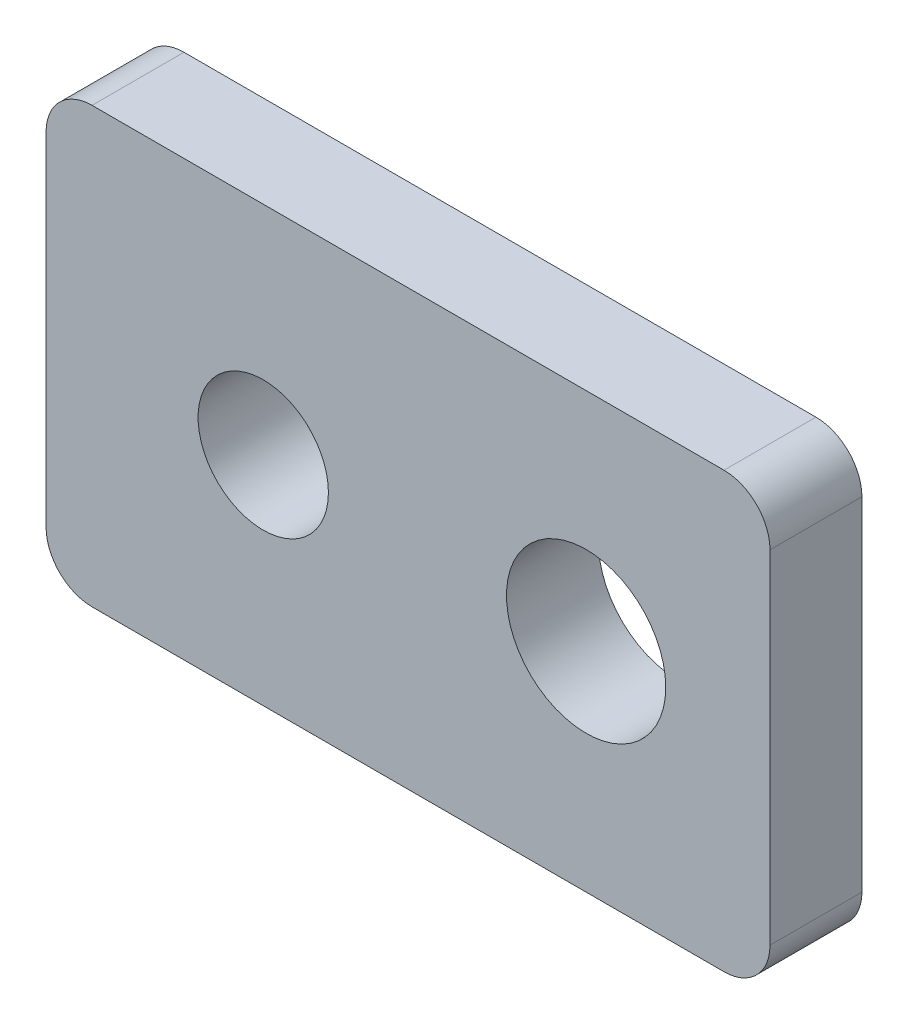
SolidWorks part; units mm, degrees
material "3003-H14"
ref_plane "X-Y Datum" through (0, 0, 0) normal (0, 0, 1) x (1, 0, 0)
ref_plane "X-Z Datum" through (0, 0, 0) normal (0, 1, 0) x (1, 0, 0)
ref_plane "Y-Z Datum" through (0, 0, 0) normal (1, 0, 0) x (0, 0, -1)
sketch "Sketch1" plane through (0, 0, 0) normal (0, 0, 1) x (1, 0, 0)
  line L0 (6.15, 7.5) -> (6.15, -7.5) construction
  line L1 (-12.5, 7.5) -> (12.5, 7.5)
  line L2 (-12.5, 7.5) -> (-12.5, -7.5)
  line L3 (-12.5, -7.5) -> (12.5, -7.5)
  line L4 (12.5, 7.5) -> (12.5, -7.5)
  line L5 (-12.5, 7.5) -> (12.5, -7.5) construction
  line L6 (-12.5, -7.5) -> (12.5, 7.5) construction
  line L7 (-12.5, 0) -> (12.5, 0) construction
  circle A0 centre (6.15, 0) radius 2.5
  point P0 (0, 0)
  dimension "D3" = 5
  dimension "D4" = 6.35
  dimension "D1" = 15
  dimension "D2" = 25
extrude "Boss-Extrude1" add sketch "Sketch1" along normal blind 3.175 contours A0 | L4 L1 L2 L3 A0
hole_wizard "M5 Clearance Hole1" positions "Sketch4" profile "Sketch3" hole size "M5" standard "ANSI Metric" end condition through all
sketch "Sketch4" plane through (0, 0, 3.175) normal (0, 0, 1) x (1, 0, 0)
  point P0 (6.15, 0)
sketch "Sketch3" plane through (6.15, 0, 3.175) normal (1, 0, 0) x (0, -1, 0)
  line L0 (0, 0) -> (0, 3.175)
  line L1 (0, 3.175) -> (2.75, 3.175)
  line L2 (2.75, 3.175) -> (2.75, 0)
  line L5 (2.75, 0) -> (0, 0)
  line L11 (0, -6.35) -> (0, 107.95) construction
  dimension "Thru Hole Dia." = 5.5
  dimension "Thru Hole Depth" = 3.175
fillet "Fillet1" radius 1.5875 4 edges at (-12.5, 7.5, 1.5875) (-12.5, -7.5, 1.5875) (12.5, 7.5, 1.5875) (12.5, -7.5, 1.5875)
sketch "Sketch5" plane through (0, 0, 3.175) normal (0, 0, 1) x (1, 0, 0)
  line L0 (-4, -2) -> (-6, -2) construction
  line L1 (-4, 2) -> (-6, 2) construction
  line L2 (-4, -2) -> (-6, -2)
  line L3 (-4, 2) -> (-6, 2)
  line L12 (-5, 2) -> (-5, -2)
  arc A0 (-4, -2) -> (-4, 2) centre (-4, 0) ccw construction
  arc A1 (-6, 2) -> (-6, -2) centre (-6, 0) ccw construction
  arc A2 (-4, -2) -> (-4, 2) centre (-4, 0) ccw
  arc A3 (-6, 2) -> (-6, -2) centre (-6, 0) ccw
  point P8 (-5, 0)
  point P10 (-5, 0)
hole_wizard "M4 Clearance Hole2" positions "Sketch9" profile "Sketch8" hole size "M4" standard "ANSI Metric" end condition through all
sketch "Sketch9" plane through (0, 0, 3.175) normal (0, 0, 1) x (1, 0, 0)
  point P3 (-5, 0)
sketch "Sketch8" plane through (-5, 0, 3.175) normal (1, 0, 0) x (0, -1, 0)
  line L0 (0, 0) -> (0, 3.175)
  line L1 (0, 3.175) -> (2.25, 3.175)
  line L2 (2.25, 3.175) -> (2.25, 0)
  line L5 (2.25, 0) -> (0, 0)
  line L11 (0, -6.35) -> (0, 107.95) construction
  dimension "Thru Hole Dia." = 4.5
  dimension "Thru Hole Depth" = 3.175
